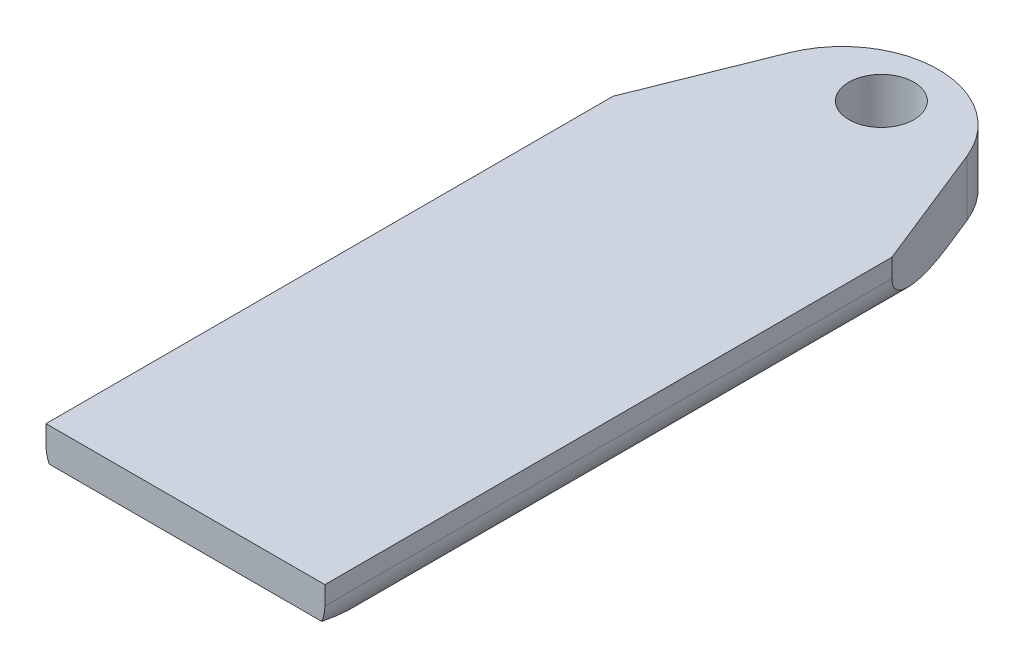
SolidWorks part; units mm, degrees
ref_plane "Alzado" through (0, 0, 0) normal (0, 0, 1) x (1, 0, 0)
ref_plane "Planta" through (0, 0, 0) normal (0, 1, 0) x (1, 0, 0)
ref_plane "Vista lateral" through (0, 0, 0) normal (1, 0, 0) x (0, 0, -1)
sketch "Croquis1" plane through (0, 0, 0) normal (0, 0, 1) x (1, 0, 0)
  line L1 (-7.5, 107) -> (7.5, 107)
  line L2 (-7.5, 107) -> (-7.5, 110)
  line L3 (-7.5, 110) -> (7.5, 110)
  line L4 (7.5, 107) -> (7.5, 110)
extrude "Saliente-Extruir1" add sketch "Croquis1" against normal blind 40.5
sketch "Croquis2" plane through (0, 107, 0) normal (0, -1, 0) x (1, 0, 0)
  line L4 (7.5, 0) -> (-7.5, 0)
  line L5 (-7.5, 0) -> (-7.5, -40.5)
  line L6 (-7.5, -40.5) -> (7.5, -40.5)
  line L7 (7.5, -40.5) -> (7.5, 0)
  line L8 (7.5, 0) -> (-7.5, 0)
  line L9 (-7.5, 0) -> (-7.5, -40.5)
  line L10 (-7.5, -40.5) -> (7.5, -40.5)
  line L11 (7.5, -40.5) -> (7.5, 0)
  circle A0 centre (-0.0655, -37.5) radius 1.75
  dimension "D3" = 3.5
  dimension "D1" = 0
extrude "Cortar-Extruir1" cut sketch "Croquis2" against normal blind 40.5 flip side to cut
chamfer "Chaflán1" distance 4 distance2 1.2 1 edges at (0, 107, 0)
chamfer "Chaflán2" distance 4 distance2 10 2 edges at (-7.5, 108.5, -40.5) (7.5, 108.5, -40.5)
fillet "Redondeo1" radius 2 2 edges at (-7.5, 107, -17.25) (7.5, 107, -17.25)
fillet "Redondeo2" radius 5.1696 4 edges at (0, 107, -40.5) (0, 110, -40.5) (3.5, 108.5, -40.5) (-3.5, 108.5, -40.5)
